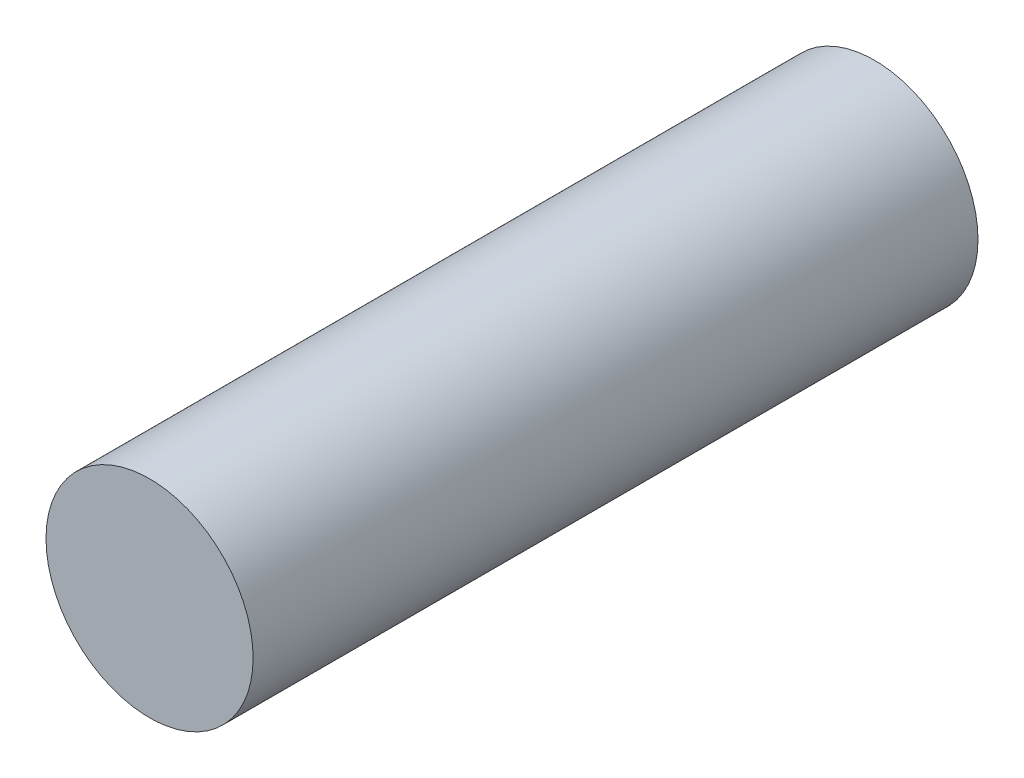
SolidWorks part; units mm, degrees
ref_plane "Front Plane" through (0, 0, 0) normal (0, 0, 1) x (1, 0, 0)
ref_plane "Top Plane" through (0, 0, 0) normal (0, 1, 0) x (1, 0, 0)
ref_plane "Right Plane" through (0, 0, 0) normal (1, 0, 0) x (0, 0, -1)
sketch "Sketch1" plane through (0, 0, 0) normal (0, 0, 1) x (1, 0, 0)
  circle A0 centre (0, 0) radius 1
  dimension "D1" = 2
extrude "Boss-Extrude1" add sketch "Sketch1" along normal blind 7
